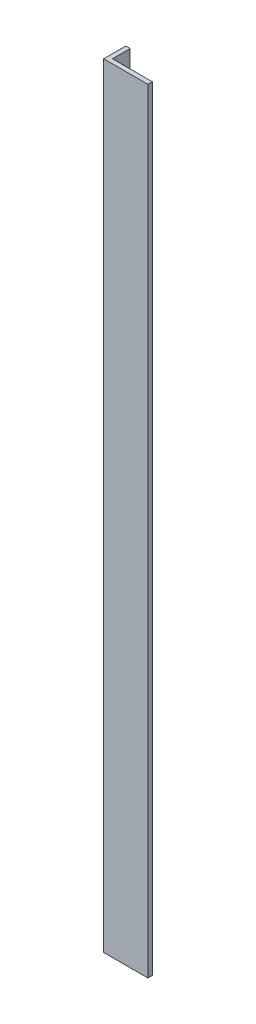
SolidWorks part; units mm, degrees
ref_plane "Front Plane" through (0, 0, 0) normal (0, 0, 1) x (1, 0, 0)
ref_plane "Top Plane" through (0, 0, 0) normal (0, 1, 0) x (1, 0, 0)
ref_plane "Right Plane" through (0, 0, 0) normal (1, 0, 0) x (0, 0, -1)
sketch "Sketch1" plane through (0, 0, 0) normal (0, 1, 0) x (1, 0, 0)
  line L0 (0, 0) -> (0, 10)
  line L1 (0, 10) -> (2, 10)
  line L2 (2, 10) -> (2, 2)
  line L3 (2, 2) -> (20, 2)
  line L4 (20, 2) -> (20, 0)
  line L5 (20, 0) -> (0, 0)
extrude "Boss-Extrude1" add sketch "Sketch1" along normal up to surface (350 mm away)
hole_wizard "Ø3.0 (3) Diameter Hole2" positions "Sketch4" profile "Sketch5" hole size "Ø3.0" standard "ISO"
sketch "Sketch4" plane through (0, -11.4076, -241.32) normal (-1, 0, 0) x (0, 0, 1)
  point P0 (235.32, 341.4076)
  point P2 (235.32, 355.4076)
  point P7 (0, 0)
  point P8 (0, 0)
  point P9 (235.32, 353.6335)
  point P10 (0, 0)
sketch "Sketch5" plane through (0, 330, -6) normal (0, 1, 0) x (0, 0, 1)
  line L0 (0, 0) -> (0, 1.999)
  line L1 (0, 1.999) -> (1.5, 1.999)
  line L2 (1.5, 1.999) -> (1.5, 0)
  line L3 (1.5, 0) -> (0, 0)
  line L4 (0, -6.35) -> (0, 107.95) construction
  dimension "Thru Hole Dia." = 3
  dimension "Thru Hole Depth" = 1.999
hole_wizard "Ø3.0 (3) Diameter Hole3" positions "Sketch6" profile "Sketch7" hole size "Ø3.0" standard "ISO"
sketch "Sketch6" plane through (0, -11.4076, -241.32) normal (-1, 0, 0) x (0, 0, 1)
  point P0 (235.6632, 17.4076)
  point P1 (235.32, 31.4034)
sketch "Sketch7" plane through (0, 6, -5.6569) normal (0, 1, 0) x (0, 0, 1)
  line L0 (0, 0) -> (0, 1.999)
  line L1 (0, 1.999) -> (1.5, 1.999)
  line L2 (1.5, 1.999) -> (1.5, 0)
  line L3 (1.5, 0) -> (0, 0)
  line L4 (0, -6.35) -> (0, 107.95) construction
  dimension "Thru Hole Dia." = 3
  dimension "Thru Hole Depth" = 1.999
